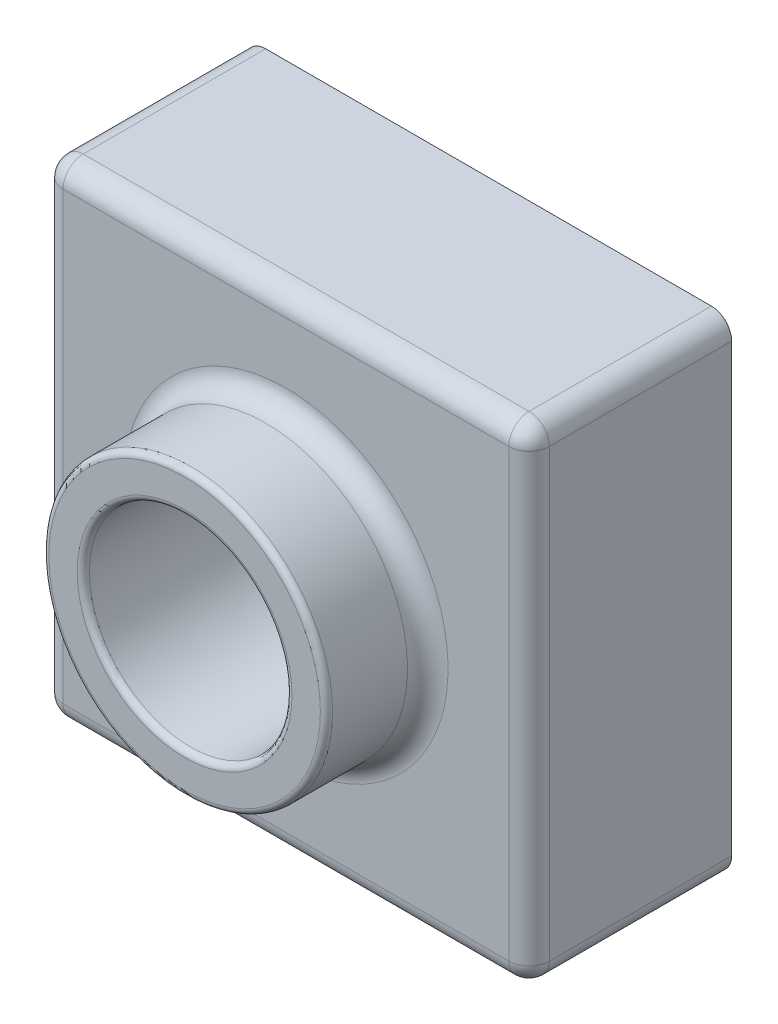
SolidWorks part; units mm, degrees
ref_plane "Front Plane" through (0, 0, 0) normal (0, 0, 1) x (1, 0, 0)
ref_plane "Top Plane" through (0, 0, 0) normal (0, 1, 0) x (1, 0, 0)
ref_plane "Right Plane" through (0, 0, 0) normal (1, 0, 0) x (0, 0, -1)
sketch "Sketch1" plane through (0, 0, 0) normal (0, 0, 1) x (1, 0, 0)
  line L1 (0, 0) -> (120, 0)
  line L2 (0, 0) -> (0, 120)
  line L3 (0, 120) -> (120, 120)
  line L4 (120, 0) -> (120, 120)
  dimension "D1" = 120
  dimension "D2" = 120
extrude "Boss-Extrude1" add sketch "Sketch1" along normal blind 50
sketch "Sketch2" plane through (0, 0, 50) normal (0, 0, 1) x (1, 0, 0)
  line L0 (120, 120) -> (0, 120) construction
  line L1 (120, 0) -> (120, 120) construction
  circle A0 centre (60, 60) radius 35
  dimension "D1" = 70
  dimension "D2" = 60
  dimension "D3" = 60
extrude "Boss-Extrude2" add sketch "Sketch2" along normal blind 25
sketch "Sketch3" plane through (0, 0, 75) normal (0, 0, 1) x (1, 0, 0)
  circle A0 centre (60, 60) radius 25
  dimension "D1" = 50
extrude "Cut-Extrude1" cut sketch "Sketch3" against normal through all
fillet "Fillet1" radius 5 9 edges at (60, 120, 50) (120, 60, 50) (60, 0, 50) (0, 60, 50) (25, 60, 50) (0, 0, 25) (120, 0, 25) (120, 120, 25) (0, 120, 25)
fillet "Fillet2" radius 1.5 2 edges at (95, 60, 75) (85, 60, 75)
